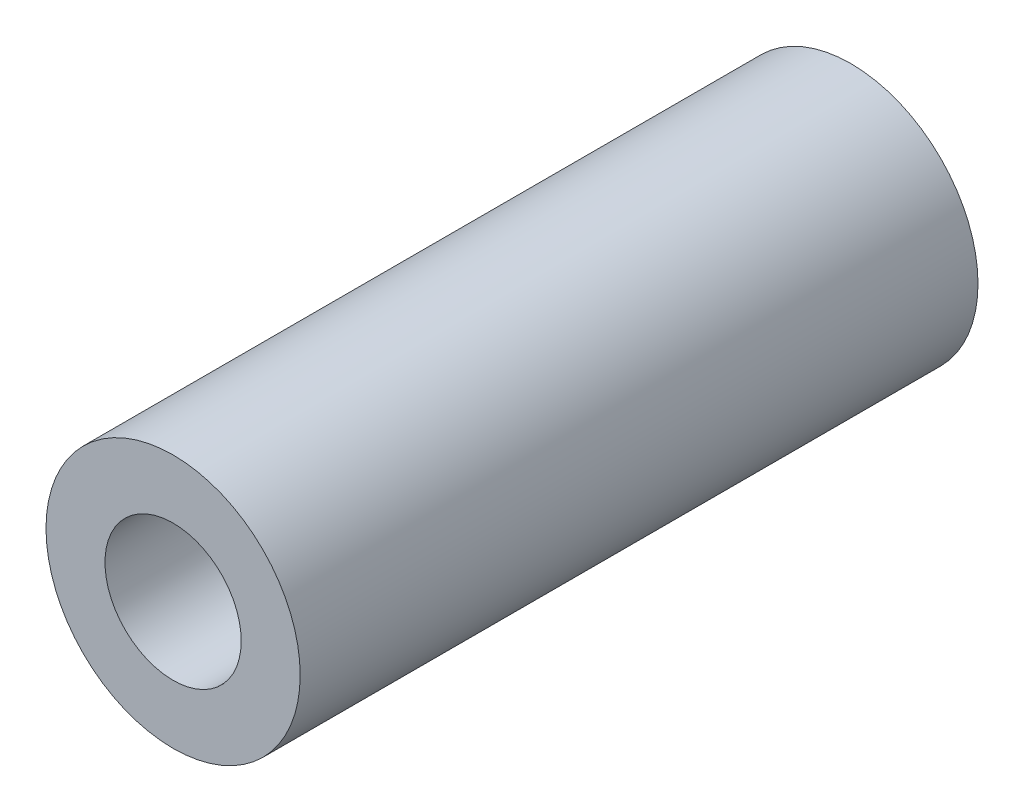
SolidWorks part; units mm, degrees
material "6061-T6 (SS)"
ref_plane "Front Plane" through (0, 0, 0) normal (0, 0, 1) x (1, 0, 0)
ref_plane "Top Plane" through (0, 0, 0) normal (0, 1, 0) x (1, 0, 0)
ref_plane "Right Plane" through (0, 0, 0) normal (1, 0, 0) x (0, 0, -1)
sketch "Sketch1" plane through (0, 0, 0) normal (0, 0, 1) x (1, 0, 0)
  circle A0 centre (0, 0) radius 4.7625
  dimension "D1" = 9.525
extrude "Boss-Extrude1" add sketch "Sketch1" along normal blind 25.4
hole_wizard "#10 Clearance Hole1" positions "Sketch2" profile "Sketch3" hole size "#10" standard "ANSI Inch" end condition through all
sketch "Sketch2" plane through (0, 0, 25.4) normal (0, 0, 1) x (1, 0, 0)
  point P0 (0, 0)
sketch "Sketch3" plane through (0, 0, 25.4) normal (1, 0, 0) x (0, -1, 0)
  line L0 (0, 0) -> (0, 25.4)
  line L1 (0, 25.4) -> (2.5527, 25.4)
  line L2 (2.5527, 25.4) -> (2.5527, 0)
  line L5 (2.5527, 0) -> (0, 0)
  line L11 (0, -6.35) -> (0, 107.95) construction
  dimension "Thru Hole Dia." = 5.1054
  dimension "Thru Hole Depth" = 25.4
